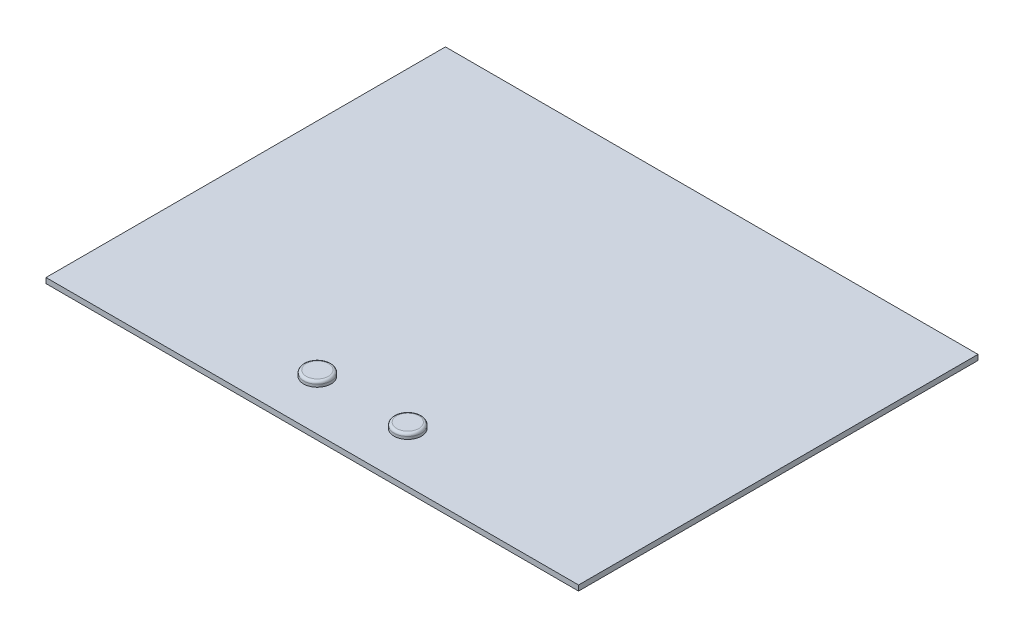
SolidWorks part; units mm, degrees
ref_plane "Front Plane" through (0, 0, 0) normal (0, 0, 1) x (1, 0, 0)
ref_plane "Top Plane" through (0, 0, 0) normal (0, 1, 0) x (1, 0, 0)
ref_plane "Right Plane" through (0, 0, 0) normal (1, 0, 0) x (0, 0, -1)
sketch "Sketch1" plane through (0, 0, 0) normal (0, 1, 0) x (1, 0, 0)
  line L1 (0, 0) -> (40, 0)
  line L2 (0, 0) -> (0, 30)
  line L3 (0, 30) -> (40, 30)
  line L4 (40, 0) -> (40, 30)
  dimension "D1" = 30
  dimension "D2" = 40
extrude "Boss-Extrude1" add sketch "Sketch1" along normal blind 0.4
sketch "Sketch2" plane through (0, 0.4, 0) normal (0, 1, 0) x (1, 0, 0)
  line L0 (20, 30) -> (20, 0) construction
  line L1 (40, 30) -> (0, 30) construction
  line L2 (0, 0) -> (40, 0) construction
  circle A0 centre (16.604, 3.7772) radius 1.0303
  circle A1 centre (23.396, 3.7772) radius 1.0303
  dimension "D1" = 2.0606
extrude "Boss-Extrude2" add sketch "Sketch2" along normal blind 0.4
fillet "Fillet1" radius 0.2 2 edges at (23.396, 0.8, -4.8075) (16.604, 0.8, -2.7469)
